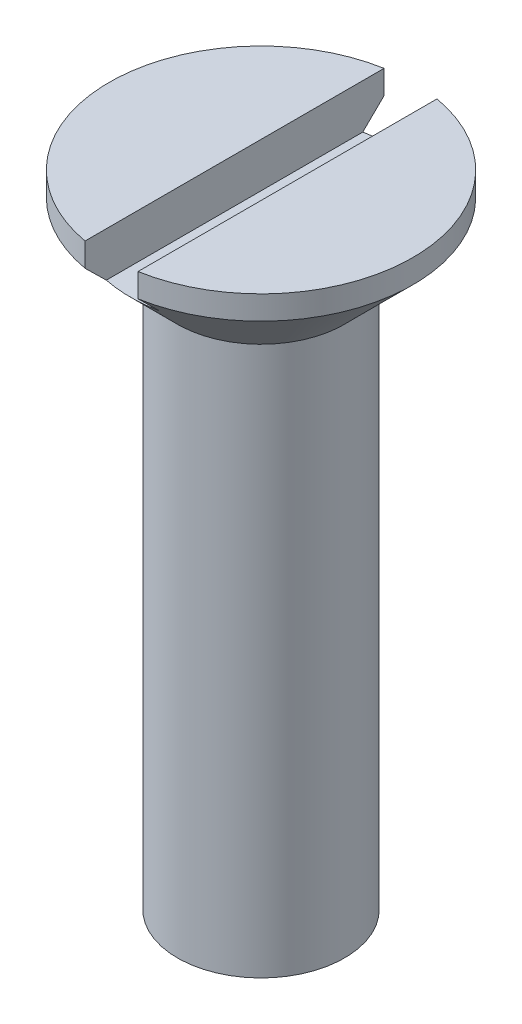
SolidWorks part; units mm, degrees
ref_plane "Front Plane" through (0, 0, 0) normal (0, 0, 1) x (1, 0, 0)
ref_plane "Top Plane" through (0, 0, 0) normal (0, 1, 0) x (1, 0, 0)
ref_plane "Right Plane" through (0, 0, 0) normal (1, 0, 0) x (0, 0, -1)
sketch "Sketch1" plane through (0, 0, 0) normal (0, 0, 1) x (1, 0, 0)
  line L0 (0, 0) -> (0, 23) construction
  line L1 (0, 23) -> (-5.45, 23)
  line L2 (-5.45, 23) -> (-5.45, 22.15)
  line L3 (-5.45, 22.15) -> (-3, 19.7)
  line L4 (-3, 19.7) -> (-3, 0)
  line L5 (0, -1.7321) -> (0, 0) construction
  line L6 (-3, 0) -> (0, -1.7321)
  line L7 (0, 23) -> (0, -1.7321)
  dimension "D1" = 10.9
  dimension "D2" = 23
  dimension "D3" = 3
  dimension "D4" = 3.3
  dimension "D5" = 45
  dimension "D6" = 60
revolve "Revolve1" add sketch "Sketch1" angle 360 about L7
sketch "Sketch2" plane through (0, 0, 0) normal (0, 0, 1) x (1, 0, 0)
  line L0 (5.45, 23) -> (-5.45, 23) construction
  line L1 (-0.95, 23) -> (0.95, 23)
  line L2 (-0.95, 23) -> (-0.95, 21.4)
  line L3 (-0.95, 21.4) -> (0.95, 21.4)
  line L4 (0.95, 23) -> (0.95, 21.4)
  point P6 (0, 23)
  dimension "D1" = 1.9
  dimension "D2" = 1.6
extrude "Cut-Extrude1" cut sketch "Sketch2" against normal through all both and the other way through all
